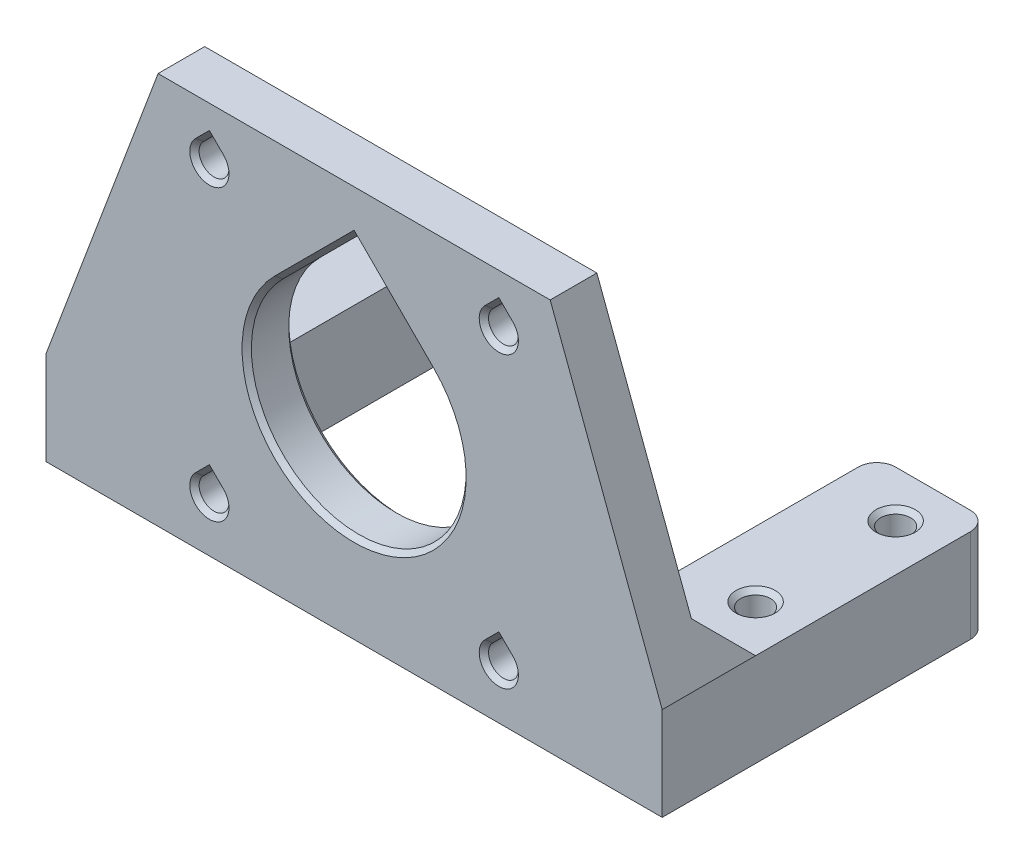
SolidWorks part; units mm, degrees
ref_plane "前视基准面" through (0, 0, 0) normal (0, 0, 1) x (1, 0, 0)
ref_plane "上视基准面" through (0, 0, 0) normal (0, 1, 0) x (1, 0, 0)
ref_plane "右视基准面" through (0, 0, 0) normal (1, 0, 0) x (0, 0, -1)
sketch "草图1" plane through (0, 0, 0) normal (0, 0, 1) x (1, 0, 0)
  line L0 (0, 425.6245) -> (0, -425.6245) construction
  line L1 (-425.6245, 0) -> (425.6245, 0) construction
  line L2 (-15.5, 15.5) -> (-15.5, 17.7627) construction
  line L3 (15.5, 15.5) -> (-15.5, 15.5) construction
  line L4 (15.5, 15.5) -> (15.5, -15.5) construction
  line L5 (15.5, -15.5) -> (-15.5, -15.5) construction
  line L6 (-15.5, 15.5) -> (-15.5, -15.5) construction
  line L7 (15.5, 15.5) -> (-15.5, -15.5) construction
  line L8 (15.5, -15.5) -> (-15.5, 15.5) construction
  line L9 (-15.5, 17.7627) -> (-16.6314, 16.6314)
  line L10 (-15.5, 17.7627) -> (-14.3686, 16.6314)
  line L11 (-15.5, -13.2373) -> (-16.6314, -14.3686)
  line L12 (-15.5, -13.2373) -> (-14.3686, -14.3686)
  line L13 (-8.1317, 8.1317) -> (0, 16.2635)
  line L14 (8.1317, 8.1317) -> (0, 16.2635)
  line L15 (15.5, 15.5) -> (15.5, -15.5) construction
  line L16 (15.5, 15.5) -> (15.5, 17.7627) construction
  line L17 (15.5, -13.2373) -> (14.3686, -14.3686)
  line L18 (15.5, -13.2373) -> (16.6314, -14.3686)
  line L19 (15.5, 17.7627) -> (14.3686, 16.6314)
  line L20 (15.5, 17.7627) -> (16.6314, 16.6314)
  line L21 (-21, 21) -> (21, 21)
  line L22 (21, 21) -> (-21, 21) construction
  line L23 (21, 21) -> (21, -21) construction
  line L24 (21, -21) -> (-21, -21) construction
  line L25 (-21, 21) -> (-21, -21) construction
  line L26 (21, 21) -> (-21, -21) construction
  line L27 (21, -21) -> (-21, 21) construction
  line L28 (21, 21) -> (21, -11)
  line L29 (21, -11) -> (33, -11)
  line L30 (33, -11) -> (33, -21)
  line L31 (33, -21) -> (-33, -21)
  line L32 (-33, -21) -> (-33, -11)
  line L33 (-33, -11) -> (-21, -11)
  line L34 (-21, -11) -> (-21, 21)
  arc A0 (-8.1317, 8.1317) -> (8.1317, 8.1317) centre (0, 0) ccw
  arc A1 (-16.6314, -14.3686) -> (-14.3686, -14.3686) centre (-15.5, -15.5) ccw
  arc A2 (-16.6314, 16.6314) -> (-14.3686, 16.6314) centre (-15.5, 15.5) ccw
  arc A3 (16.6314, 16.6314) -> (14.3686, 16.6314) centre (15.5, 15.5) cw
  arc A4 (16.6314, -14.3686) -> (14.3686, -14.3686) centre (15.5, -15.5) cw
  dimension "D1" = 23
  dimension "D4" = 3.2
  dimension "D2" = 31
  dimension "D3" = 31
  dimension "D5" = 45
  dimension "D6" = 42
  dimension "D7" = 42
  dimension "D8" = 10
  dimension "D9" = 10
  dimension "D10" = 12
  dimension "D11" = 12
extrude "凸台-拉伸1" add sketch "草图1" along normal blind 5
sketch "草图2" plane through (0, 0, 0) normal (0, 0, -1) x (-1, 0, 0)
  line L0 (-21, -11) -> (-21, -21)
  line L1 (33, -21) -> (-33, -21) construction
  line L2 (-21, -21) -> (-33, -21)
  line L3 (-33, -21) -> (-33, -11)
  line L4 (-33, -11) -> (-21, -11)
  line L5 (21, -11) -> (33, -11)
  line L6 (33, -11) -> (33, -21)
  line L7 (33, -21) -> (21, -21)
  line L8 (21, -21) -> (21, -11)
extrude "凸台-拉伸2" add sketch "草图2" along normal blind 30
sketch "草图3" plane through (0, 0, 5) normal (0, 0, 1) x (1, 0, 0)
  line L0 (-21, 21) -> (-33, -11)
  line L1 (-33, -11) -> (-21, -11)
  line L2 (-21, -11) -> (-21, 21)
  line L3 (0, 0) -> (0, 37.4036) construction
  line L4 (21, -11) -> (21, 21)
  line L5 (33, -11) -> (21, -11)
  line L6 (21, 21) -> (33, -11)
extrude "凸台-拉伸3" add sketch "草图3" against normal blind 5
sketch "草图5" plane through (0, -11, 0) normal (0, 1, 0) x (1, 0, 0)
  line L0 (28, 30) -> (28, 0) construction
  line L1 (21, 30) -> (33, 30) construction
  line L2 (0, 0) -> (0, 85.1891) construction
  line L3 (21, 0) -> (-21, 0) construction
  line L4 (33, 0) -> (33, 30) construction
  line L5 (21, 0) -> (33, 0) construction
  line L6 (-28, 30) -> (-28, 0) construction
  circle A0 centre (28, 25) radius 1.6
  circle A1 centre (28, 10) radius 1.6
  circle A2 centre (-28, 10) radius 1.6
  circle A3 centre (-28, 25) radius 1.6
  dimension "D2" = 3.2
  dimension "D1" = 5
  dimension "D3" = 10
  dimension "D4" = 5
extrude "切除-拉伸1" cut sketch "草图5" against normal through all
fillet "圆角1" radius 2 4 edges at (-33, -16, -30) (-21, -16, -30) (33, -16, -30) (21, -16, -30)
chamfer "倒角1" distance 5 angle 45 2 edges at (27, -11, 0) (-27, -11, 0)
chamfer "倒角2" distance 0.5 angle 45 38 edges at (14.9343, 17.1971, 5) (16.0657, 17.1971, 5) (15.5, 13.9, 5) (14.9343, 17.1971, 0) (16.0657, 17.1971, 0) (15.5, 13.9, 0) (-16.0657, 17.1971, 5) (-14.9343, 17.1971, 5) (-15.5, 13.9, 5) (-16.0657, 17.1971, 0) (-14.9343, 17.1971, 0) (-15.5, 13.9, 0) (-16.0657, -13.8029, 5) (-14.9343, -13.8029, 5) (-15.5, -17.1, 5) (-16.0657, -13.8029, 0) (-14.9343, -13.8029, 0) (-15.5, -17.1, 0) (14.9343, -13.8029, 5) (16.0657, -13.8029, 5) (15.5, -17.1, 5) (14.9343, -13.8029, 0) (16.0657, -13.8029, 0) (15.5, -17.1, 0) (-4.0659, 12.1976, 5) (4.0659, 12.1976, 5) (0, -11.5, 5) (-4.0659, 12.1976, 0) (4.0659, 12.1976, 0) (0, -11.5, 0) (-28, -11, -26.6) (-28, -21, -26.6) (-28, -11, -11.6) (-28, -21, -11.6) (28, -11, -23.4) (28, -21, -23.4) (28, -11, -8.4) (28, -21, -8.4)
